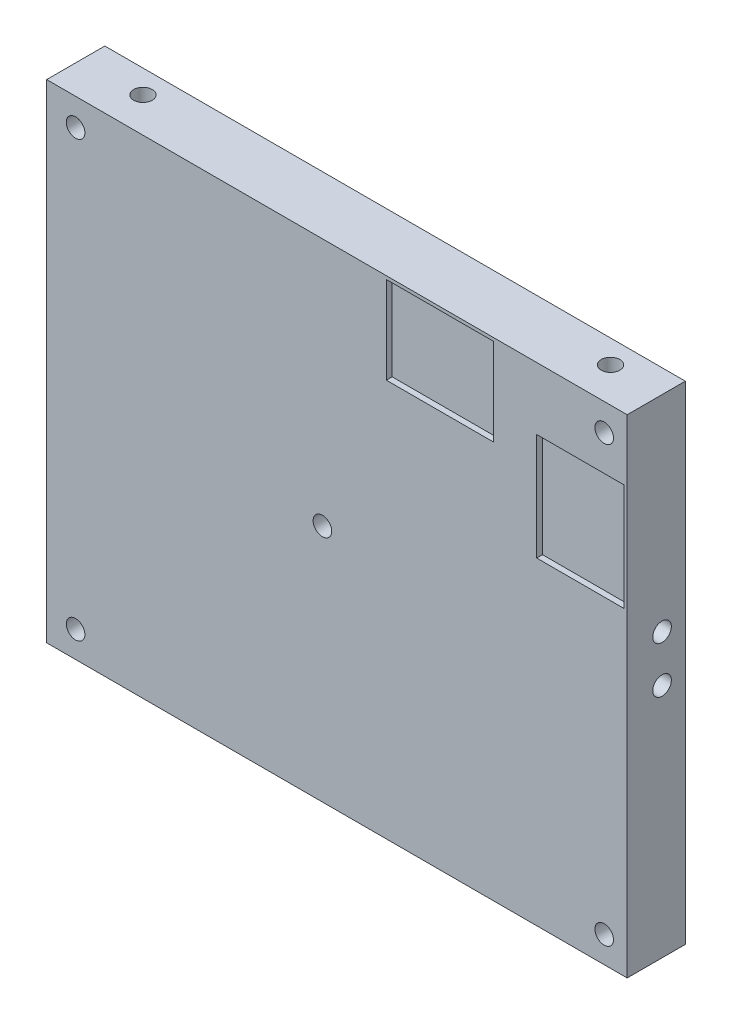
SolidWorks part; units mm, degrees
material "6061-T6 (SS)"
ref_plane "前视基准面" through (0, 0, 0) normal (0, 0, 1) x (1, 0, 0)
ref_plane "上视基准面" through (0, 0, 0) normal (0, 1, 0) x (1, 0, 0)
ref_plane "右视基准面" through (0, 0, 0) normal (1, 0, 0) x (0, 0, -1)
other "Configuration Table"
sketch "草图1" plane through (0, 0, 0) normal (0, 0, 1) x (1, 0, 0)
  line L1 (-4.3, -4.3) -> (53.65, -4.3)
  line L2 (-4.3, -4.3) -> (-4.3, 45.68)
  line L3 (-4.3, 45.68) -> (53.65, 45.68)
  line L4 (53.65, -4.3) -> (53.65, 45.68)
  dimension "D1" = 53.65
  dimension "D2" = 4.3
  dimension "D3" = 45.68
  dimension "D4" = 4.3
extrude "Main_Stock" add sketch "草图1" along normal blind 5 from offset 2.7519
sketch "草图2" plane through (0, 0, 2.2481) normal (0, 0, 1) x (1, 0, 0)
  circle A0 centre (-2.3, 1) radius 1.1
  circle A1 centre (51.65, 1) radius 1.1
  circle A2 centre (12, -2.3) radius 1.1
  circle A3 centre (37.35, -2.3) radius 1.1
  circle A4 centre (3, 43.68) radius 1.1
  circle A5 centre (44, 43.68) radius 1.1
  dimension "D1" = 2.2
  dimension "D2" = 3
  dimension "D3" = 12
  dimension "D4" = 37.35
  dimension "D5" = 44
  dimension "D6" = 51.65
  dimension "D7" = 2.3
  dimension "D8" = 1
  dimension "D9" = 43.68
  dimension "D10" = 2.3
extrude "Frame_6xD2p2_Through" [suppressed] cut sketch "草图2" against normal through all
sketch "草图3" plane through (0, 0, 2.2481) normal (0, 0, 1) x (1, 0, 0)
  circle A0 centre (23.4283, 20.2768) radius 0.8
  circle A1 centre (2.2063, 39.3338) radius 0.8
  circle A2 centre (47.6533, 39.3338) radius 0.8
  circle A3 centre (47.6533, 1.9767) radius 0.8
  circle A4 centre (2.2063, 1.9767) radius 0.8
  dimension "D1" = 1.6
  dimension "D2" = 2.2063
  dimension "D3" = 23.4283
  dimension "D4" = 47.6533
  dimension "D5" = 1.9767
  dimension "D6" = 20.2768
  dimension "D7" = 39.3338
extrude "PCB_5xD1p6_M2_Through" cut sketch "草图3" against normal through all
cosmetic thread "PCB_M2_Cosmetic_1" parameters "D2"=2
cosmetic thread "PCB_M2_Cosmetic_2" parameters "D2"=2
cosmetic thread "PCB_M2_Cosmetic_3" parameters "D2"=2
cosmetic thread "PCB_M2_Cosmetic_4" parameters "D2"=2
cosmetic thread "PCB_M2_Cosmetic_5" parameters "D2"=2
sketch "草图4" plane through (-4.3, 0, 0) normal (-1, 0, 0) x (0, 0, 1)
  circle A0 centre (3.8995, 10.725) radius 2.05
  dimension "D1" = 4.1
  dimension "D2" = 3.8995
  dimension "D3" = 10.725
extrude "SMA_L_Center_Matching_Arc" [suppressed] cut sketch "草图4" against normal blind 4
sketch "草图5" plane through (-4.3, 0, 0) normal (-1, 0, 0) x (0, 0, 1)
  circle A0 centre (-0.4005, 6.425) radius 0.875
  circle A1 centre (-0.4005, 15.025) radius 0.875
  dimension "D1" = 1.75
  dimension "D2" = 0.4005
  dimension "D3" = 6.425
  dimension "D4" = 15.025
extrude "SMA_L_Lower_2xD1p75_Blind4" [suppressed] cut sketch "草图5" against normal blind 4
cosmetic thread "SMA_L_Lower_Cosmetic_1" [suppressed] parameters "D1"=3.5, "D2"=2.2
cosmetic thread "SMA_L_Lower_Cosmetic_2" [suppressed] parameters "D1"=3.5, "D2"=2.2
sketch "草图6" plane through (53.65, 0, 0) normal (1, 0, 0) x (0, 0, -1)
  circle A0 centre (-3.8995, 10.725) radius 2.05
  dimension "D1" = 4.1
  dimension "D2" = 3.8995
  dimension "D3" = 10.725
extrude "SMA_R_Center_Matching_Arc" [suppressed] cut sketch "草图6" against normal blind 4
sketch "草图7" plane through (53.65, 0, 0) normal (1, 0, 0) x (0, 0, -1)
  circle A0 centre (0.4005, 6.425) radius 0.875
  circle A1 centre (0.4005, 15.025) radius 0.875
  dimension "D1" = 1.75
  dimension "D2" = 0.4005
  dimension "D3" = 6.425
  dimension "D4" = 15.025
extrude "SMA_R_Lower_2xD1p75_Blind4" [suppressed] cut sketch "草图7" against normal blind 4
cosmetic thread "SMA_R_Lower_Cosmetic_1" [suppressed] parameters "D1"=3.5, "D2"=2.2
cosmetic thread "SMA_R_Lower_Cosmetic_2" [suppressed] parameters "D1"=3.5, "D2"=2.2
sketch "草图8" plane through (53.65, 0, 0) normal (1, 0, 0) x (0, 0, -1)
  line L1 (-0.9, 25.9) -> (-7.6, 25.9)
  line L2 (-0.9, 25.9) -> (-0.9, 37.4)
  line L3 (-0.9, 37.4) -> (-7.6, 37.4)
  line L4 (-7.6, 25.9) -> (-7.6, 37.4)
  dimension "D1" = 0.9
  dimension "D2" = 7.6
  dimension "D3" = 25.9
  dimension "D4" = 37.4
extrude "Right_TypeC_Window_Lower" [suppressed] cut sketch "草图8" against normal blind 4
sketch "草图9" plane through (0, 45.68, 0) normal (0, 1, 0) x (1, 0, 0)
  line L1 (6.07, -0.9) -> (39.273, -0.9)
  line L2 (6.07, -0.9) -> (6.07, -7.6)
  line L3 (6.07, -7.6) -> (39.273, -7.6)
  line L4 (39.273, -0.9) -> (39.273, -7.6)
  dimension "D1" = 6.07
  dimension "D2" = 39.273
  dimension "D3" = 0.9
  dimension "D4" = 7.6
extrude "Rear_Window_Lower" [suppressed] cut sketch "草图9" against normal blind 4
sketch "草图10" plane through (0, 0, 2.2481) normal (0, 0, 1) x (1, 0, 0)
  line L1 (41.85, 27.1) -> (49.35, 27.1)
  line L2 (41.85, 27.1) -> (41.85, 36.3)
  line L3 (41.85, 36.3) -> (49.35, 36.3)
  line L4 (49.35, 27.1) -> (49.35, 36.3)
  dimension "D1" = 41.85
  dimension "D2" = 49.35
  dimension "D3" = 27.1
  dimension "D4" = 36.3
extrude "TypeC_Bottom_Recess_A" cut sketch "草图10" against normal blind 0.5
sketch "草图11" plane through (0, 0, 2.2481) normal (0, 0, 1) x (1, 0, 0)
  line L1 (28.923, 33.88) -> (38.123, 33.88)
  line L2 (28.923, 33.88) -> (28.923, 41.38)
  line L3 (28.923, 41.38) -> (38.123, 41.38)
  line L4 (38.123, 33.88) -> (38.123, 41.38)
  dimension "D1" = 28.923
  dimension "D2" = 38.123
  dimension "D3" = 33.88
  dimension "D4" = 41.38
extrude "TypeC_Bottom_Recess_B" cut sketch "草图11" against normal blind 0.5
sketch "草图12" plane through (0, 0, -2.7519) normal (0, 0, -1) x (-1, 0, 0)
  line L1 (6, -6) -> (-56, -6)
  line L2 (6, -6) -> (6, 48)
  line L3 (6, 48) -> (-56, 48)
  line L4 (-56, -6) -> (-56, 48)
  line L6 (0.28, -0.28) -> (-49.63, -0.28)
  line L7 (0.28, -0.28) -> (0.28, 41.66)
  line L8 (0.28, 41.66) -> (-49.63, 41.66)
  line L9 (-49.63, -0.28) -> (-49.63, 41.66)
  dimension "D1" = 0.28
  dimension "D2" = 6
  dimension "D3" = 49.63
  dimension "D4" = 56
  dimension "D5" = 41.66
  dimension "D6" = 48
  dimension "D7" = 0.28
  dimension "D8" = 6
extrude "Inset_Base_Perimeter" cut sketch "草图12" against normal blind 5.1
sketch "草图13" plane through (-0.28, 0, 0) normal (-1, 0, 0) x (0, 0, 1)
  circle A0 centre (-0.75, 20) radius 0.8
  circle A1 centre (-0.75, 33) radius 0.8
  dimension "D1" = 1.6
  dimension "D2" = 0.75
  dimension "D3" = 20
  dimension "D4" = 33
extrude "Horizontal_Base_M2_0_-0.00028" cut sketch "草图13" against normal blind 5
cosmetic thread "装饰螺纹线1" parameters "D1"=4.5, "D2"=2
cosmetic thread "装饰螺纹线2" parameters "D1"=4.5, "D2"=2
sketch "草图14" plane through (49.63, 0, 0) normal (1, 0, 0) x (0, 0, -1)
  circle A0 centre (0.75, 20) radius 0.8
  circle A1 centre (0.75, 24) radius 0.8
  dimension "D1" = 1.6
  dimension "D2" = 0.75
  dimension "D3" = 20
  dimension "D4" = 24
extrude "Horizontal_Base_M2_0_0.04963" cut sketch "草图14" against normal blind 5
cosmetic thread "装饰螺纹线3" parameters "D1"=4.5, "D2"=2
cosmetic thread "装饰螺纹线4" parameters "D1"=4.5, "D2"=2
sketch "草图15" plane through (0, -0.28, 0) normal (0, -1, 0) x (1, 0, 0)
  circle A0 centre (14.5, -0.75) radius 0.8
  circle A1 centre (34.85, -0.75) radius 0.8
  dimension "D1" = 1.6
  dimension "D2" = 14.5
  dimension "D3" = 34.85
  dimension "D4" = 0.75
extrude "Horizontal_Base_M2_1_-0.00028" cut sketch "草图15" against normal blind 5
cosmetic thread "装饰螺纹线5" parameters "D1"=4.5, "D2"=2
cosmetic thread "装饰螺纹线6" parameters "D1"=4.5, "D2"=2
sketch "草图16" plane through (0, 41.66, 0) normal (0, 1, 0) x (1, 0, 0)
  circle A0 centre (5, 0.75) radius 0.8
  circle A1 centre (45.2, 0.75) radius 0.8
  dimension "D1" = 1.6
  dimension "D2" = 5
  dimension "D3" = 45.2
  dimension "D4" = 0.75
extrude "Horizontal_Base_M2_1_0.04166" cut sketch "草图16" against normal blind 5
cosmetic thread "装饰螺纹线7" parameters "D1"=4.5, "D2"=2
cosmetic thread "装饰螺纹线8" parameters "D1"=4.5, "D2"=2
